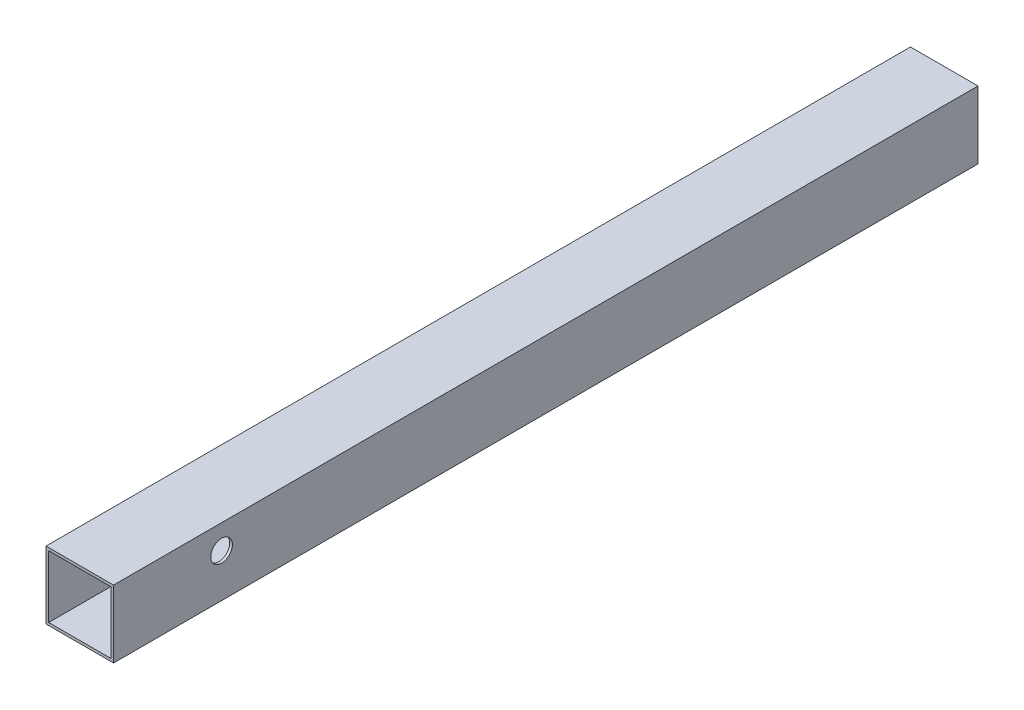
SolidWorks part; units mm, degrees
ref_plane "Front Plane" through (0, 0, 0) normal (0, 0, 1) x (1, 0, 0)
ref_plane "Top Plane" through (0, 0, 0) normal (0, 1, 0) x (1, 0, 0)
ref_plane "Right Plane" through (0, 0, 0) normal (1, 0, 0) x (0, 0, -1)
sketch "Sketch1" plane through (0, 0, 0) normal (0, 0, 1) x (1, 0, 0)
  line L0 (-11.5, 11.5) -> (11.5, 11.5)
  line L1 (-12.5, -12.5) -> (12.5, -12.5)
  line L2 (-12.5, -12.5) -> (-12.5, 12.5)
  line L3 (-12.5, 12.5) -> (12.5, 12.5)
  line L4 (12.5, -12.5) -> (12.5, 12.5)
  line L5 (-12.5, -12.5) -> (12.5, 12.5) construction
  line L6 (-12.5, 12.5) -> (12.5, -12.5) construction
  line L7 (11.5, -11.5) -> (11.5, 11.5)
  line L8 (-11.5, -11.5) -> (11.5, -11.5)
  line L9 (-11.5, -11.5) -> (-11.5, 11.5)
  point P0 (0, 0)
  dimension "D1" = 25
  dimension "D2" = 25
  dimension "D3" = 1
extrude "Boss-Extrude1" add sketch "Sketch1" along normal blind 320
sketch "Sketch2" plane through (12.5, 0, 0) normal (1, 0, 0) x (0, 0, -1)
  line L0 (-216.9003, -44.5) -> (-297.1807, -44.5) construction
  line L1 (-297.1807, 5.5) -> (-216.9003, 5.5) construction
  line L2 (-320, -12.5) -> (0, -12.5) construction
  line L3 (-281.672, -3.5) -> (-242.7482, -3.5) construction
  line L4 (-138.3828, -26.5) -> (-89.4178, -26.5) construction
  line L5 (-136.616, 3.5) -> (-94.9705, 3.5) construction
  line L7 (-320, -12.5) -> (-320, 12.5) construction
  circle A0 centre (-280, -3.5) radius 4 construction
  circle A1 centre (-280, 3.5) radius 4
  dimension "D6" = 8
  dimension "D7" = 40
  dimension "D8" = 40
  dimension "D1" = 50
  dimension "D2" = 18
  dimension "D3" = 41
  dimension "D4" = 32
  dimension "D5" = 30
extrude "Cut-Extrude1" cut sketch "Sketch2" against normal through all
